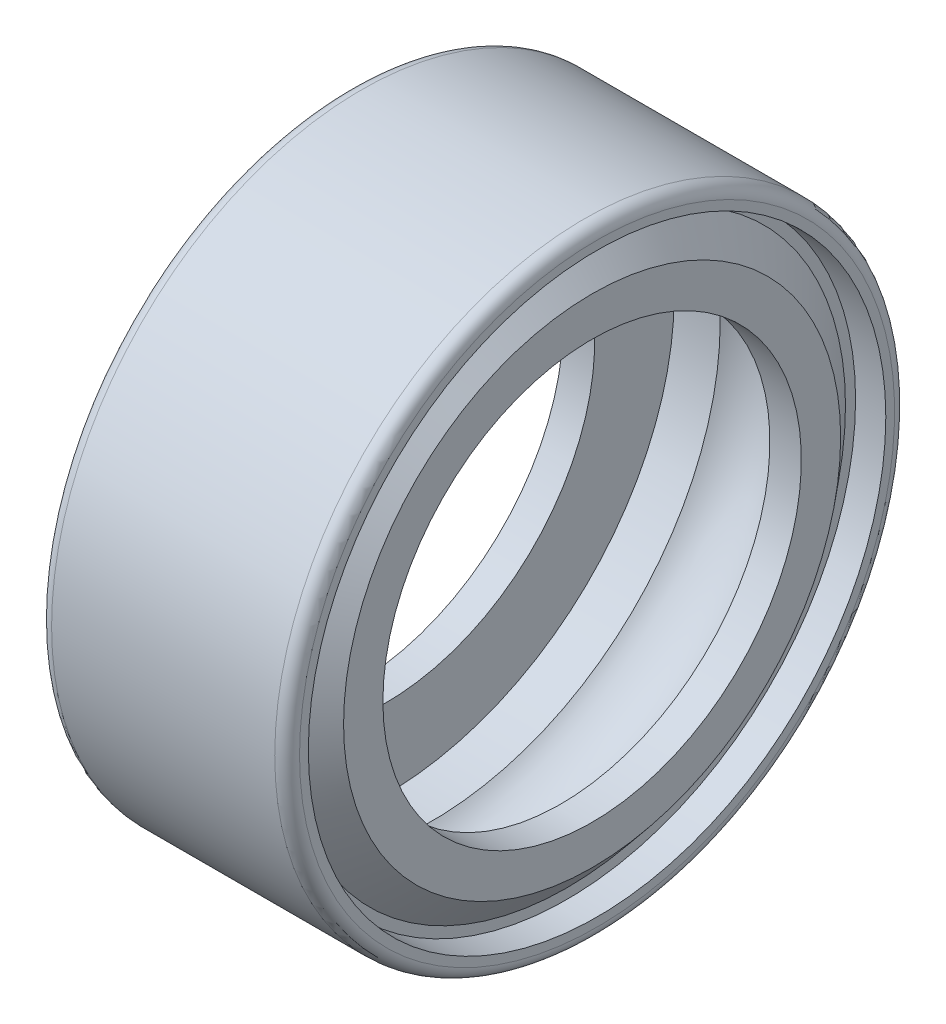
SolidWorks part; units mm, degrees
material "AISI 347 Annealed Stainless Steel (SS)"
ref_plane "Front Plane" through (0, 0, 0) normal (0, 0, 1) x (1, 0, 0)
ref_plane "Top Plane" through (0, 0, 0) normal (0, 1, 0) x (1, 0, 0)
ref_plane "Right Plane" through (0, 0, 0) normal (1, 0, 0) x (0, 0, -1)
ref_plane "Plane1" through (0, 0, 0) normal (0, 0, -1) x (-1, 0, 0)
sketch "Sketch1" plane through (0, 0, 0) normal (0, 0, -1) x (-1, 0, 0)
  line L0 (1.524, 3.1826) -> (1.2007, 3.5679)
  line L1 (1.2007, 3.5679) -> (1.2007, 3.6973)
  line L2 (1.2007, 3.6973) -> (1.5875, 3.6973)
  line L3 (1.5875, 3.6973) -> (1.5875, 3.81)
  line L4 (1.4287, 3.9688) -> (-1.4287, 3.9688)
  line L5 (-1.5875, 3.81) -> (-1.5875, 3.6973)
  line L6 (-1.5875, 3.6973) -> (-1.2007, 3.6973)
  line L7 (-1.2007, 3.6973) -> (-1.2007, 3.5679)
  line L8 (-1.2007, 3.5679) -> (-1.524, 3.1826)
  line L9 (-1.524, 3.1826) -> (-1.524, 2.6792)
  line L10 (-1.524, 2.6792) -> (-1.1213, 2.6792)
  line L11 (-1.1213, 2.6792) -> (-1.1213, 3.6973)
  line L12 (-1.1213, 3.6973) -> (-0.5328, 3.6973)
  line L13 (0.5328, 3.6973) -> (1.1213, 3.6973)
  line L14 (1.1213, 3.6973) -> (1.1213, 2.6792)
  line L15 (1.1213, 2.6792) -> (1.524, 2.6792)
  line L16 (1.524, 2.6792) -> (1.524, 3.1826)
  line L17 (-1.5875, 0) -> (1.5875, 0) construction
  arc A0 (1.5875, 3.81) -> (1.4287, 3.9688) centre (1.4287, 3.81) ccw
  arc A1 (-1.4287, 3.9688) -> (-1.5875, 3.81) centre (-1.4287, 3.81) ccw
  arc A2 (-0.5328, 3.6973) -> (0.5328, 3.6973) centre (0, 3.175) cw
revolve "Revolve1" add sketch "Sketch1" angle 360 about L17
